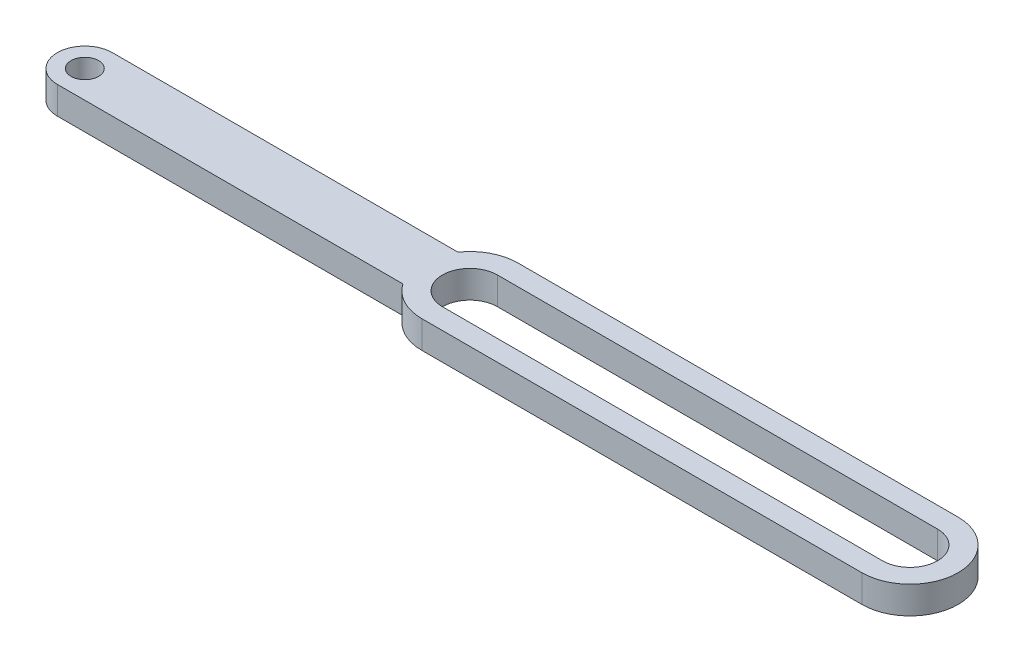
SolidWorks part; units mm, degrees
ref_plane "前视基准面" through (0, 0, 0) normal (0, 0, 1) x (1, 0, 0)
ref_plane "上视基准面" through (0, 0, 0) normal (0, 1, 0) x (1, 0, 0)
ref_plane "右视基准面" through (0, 0, 0) normal (1, 0, 0) x (0, 0, -1)
other "Configuration Table"
sketch "草图1" plane through (0, 0, 0) normal (0, 1, 0) x (1, 0, 0)
  line L0 (-30, 0) -> (30, 0) construction
  line L1 (-30, 2) -> (-4.8723, 2)
  line L2 (-30, -2) -> (-4.8723, -2)
  line L3 (-2, 3.5) -> (30, 3.5)
  line L4 (-2, -3.5) -> (30, -3.5)
  line L5 (-2, 2) -> (30, 2)
  line L6 (-2, -2) -> (30, -2)
  arc A0 (-30, 2) -> (-30, -2) centre (-30, 0) ccw
  arc A1 (30, -2) -> (30, 2) centre (30, 0) ccw
  circle A2 centre (-30, 0) radius 1
  arc A3 (-2, 3.5) -> (-4.8723, 2) centre (-2, 0) ccw
  arc A4 (30, -3.5) -> (30, 3.5) centre (30, 0) ccw
  arc A5 (-2, 2) -> (-2, -2) centre (-2, 0) ccw
  arc A6 (-4.8723, -2) -> (-2, -3.5) centre (-2, 0) ccw
  point P4 (0, 0)
  dimension "D2" = 4
  dimension "D3" = 4
  dimension "D4" = 2
  dimension "D5" = 7
  dimension "D7" = 7
  dimension "D8" = 4
  dimension "D1" = 60
  dimension "D6" = 28
extrude "凸台-拉伸1" add sketch "草图1" along normal blind 2
